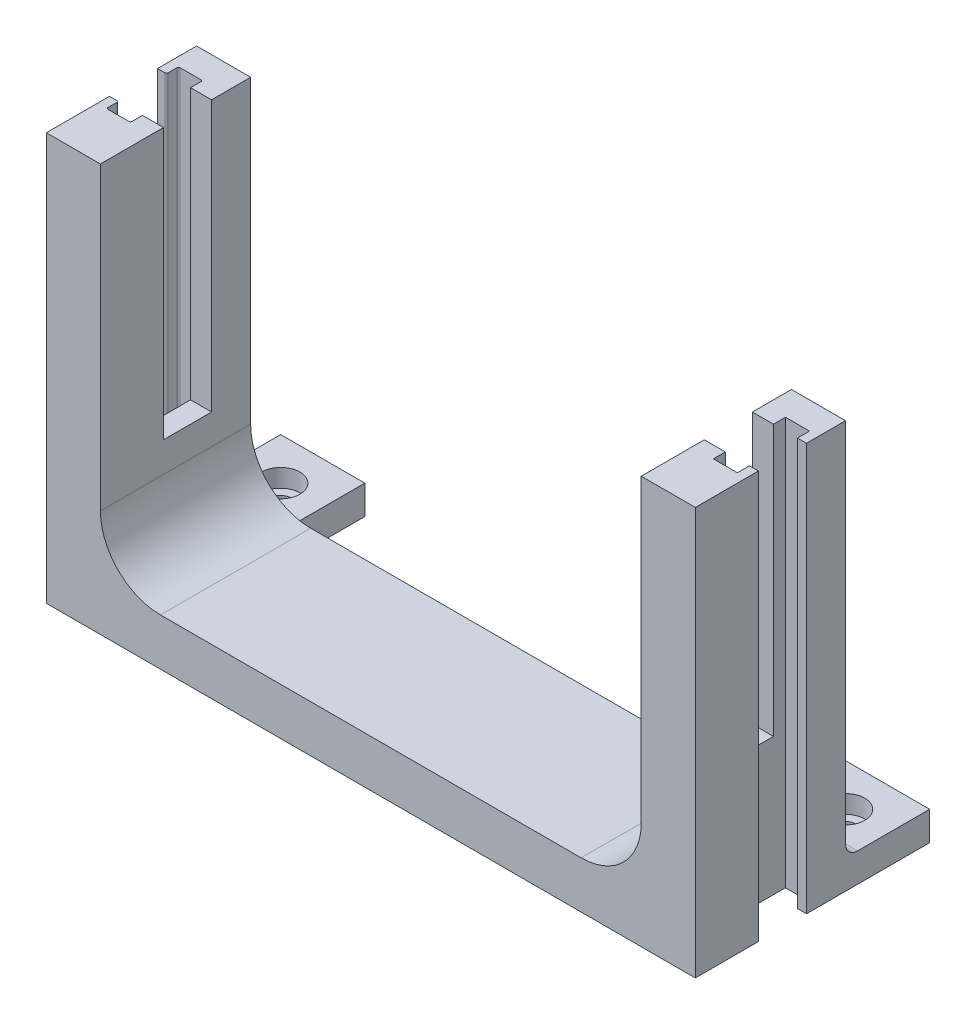
SolidWorks part; units mm, degrees
material "ABS"
ref_plane "Front Plane" through (0, 0, 0) normal (0, 0, 1) x (1, 0, 0)
ref_plane "Top Plane" through (0, 0, 0) normal (0, 1, 0) x (1, 0, 0)
ref_plane "Right Plane" through (0, 0, 0) normal (1, 0, 0) x (0, 0, -1)
sketch "Sketch1" plane through (0, 0, 0) normal (0, 0, 1) x (1, 0, 0)
  line L0 (-54, 0) -> (54, 0)
  line L1 (-54, 0) -> (-54, 67.82)
  line L2 (-54, 67.82) -> (-45, 67.82)
  line L3 (-45, 67.82) -> (-45, 7.82)
  line L4 (-45, 7.82) -> (45, 7.82)
  line L5 (0, 0) -> (0, 67.82) construction
  line L6 (54, 67.82) -> (45, 67.82)
  line L7 (45, 67.82) -> (45, 7.82)
  line L8 (54, 0) -> (54, 67.82)
  point P11 (0, 7.82)
  dimension "D1" = 45
  dimension "D2" = 60
  dimension "D3" = 7.82
  dimension "D4" = 9
extrude "Boss-Extrude1" add sketch "Sketch1" against normal blind 15
sketch "Sketch2" plane through (0, 67.82, 0) normal (0, 1, 0) x (1, 0, 0)
  line L0 (-54, 7.5) -> (-45, 7.5) construction
  line L1 (-54, 15) -> (-54, 0) construction
  line L2 (-45, 15) -> (-45, 0) construction
  line L3 (-54, 11.5) -> (-52.5, 11.5)
  line L4 (-52.5, 11.5) -> (-52.5, 13.5)
  line L5 (-52.5, 13.5) -> (-48.5, 13.5)
  line L6 (-48.5, 13.5) -> (-48.5, 1.5)
  line L7 (-54, 11.5) -> (-54, 3.5)
  line L8 (-54, 3.5) -> (-52.5, 3.5)
  line L9 (-52.5, 3.5) -> (-52.5, 1.5)
  line L10 (-52.5, 1.5) -> (-48.5, 1.5)
  point P12 (-48.5, 7.5)
  dimension "D1" = 4
  dimension "D2" = 4
  dimension "D3" = 6
  dimension "D4" = 1.5
extrude "Cut-Extrude1" cut sketch "Sketch2" against normal up to surface (67.82 mm away) up to face at (0, 0, -7.5)
sketch "Sketch3" plane through (0, 67.82, 0) normal (0, 1, 0) x (1, 0, 0)
  line L0 (-45, 11.5) -> (-48.5, 11.5)
  line L1 (-45, 15) -> (-45, 0) construction
  line L2 (-48.5, 1.5) -> (-48.5, 13.5) construction
  line L3 (-45, 3.5) -> (-48.5, 3.5)
  line L4 (-52.5, 11.5) -> (-54, 11.5) construction
  line L5 (-54, 3.5) -> (-52.5, 3.5) construction
  line L6 (-45, 11.5) -> (-45, 3.5)
  line L7 (-48.5, 11.5) -> (-48.5, 3.5)
extrude "Cut-Extrude2" cut sketch "Sketch3" against normal offset from surface (45 mm away) 15 up to face at (0, 7.82, -7.5)
fillet "Fillet1" radius 0.25 6 edges at (-52.5, 33.91, -3.5) (-52.5, 33.91, -11.5) (-52.5, 33.91, -13.5) (-48.5, 33.91, -13.5) (-52.5, 33.91, -1.5) (-48.5, 33.91, -1.5)
mirror "Mirror1" about plane through (0, 0, 0) normal (1, 0, 0) of "Cut-Extrude1"
mirror "Mirror2" about plane through (0, 0, 0) normal (1, 0, 0) of "Cut-Extrude2"
sketch "Sketch7" plane through (0, 0, 0) normal (0, 0, 1) x (1, 0, 0)
  line L8 (-54, 67.82) -> (-54, 0)
  line L9 (-54, 0) -> (54, 0)
  line L10 (54, 0) -> (54, 67.82)
  line L11 (54, 67.82) -> (45, 67.82)
  line L12 (45, 67.82) -> (45, 7.82)
  line L13 (45, 7.82) -> (-45, 7.82)
  line L14 (-45, 7.82) -> (-45, 67.82)
  line L15 (-45, 67.82) -> (-54, 67.82)
  line L16 (-54, 67.82) -> (-54, 0)
  line L17 (-54, 0) -> (54, 0)
  line L18 (54, 0) -> (54, 67.82)
  line L19 (54, 67.82) -> (45, 67.82)
  line L20 (45, 67.82) -> (45, 7.82)
  line L21 (45, 7.82) -> (-45, 7.82)
  line L22 (-45, 7.82) -> (-45, 67.82)
  line L23 (-45, 67.82) -> (-54, 67.82)
  dimension "D1" = 0
extrude "Boss-Extrude2" add sketch "Sketch7" along normal blind 7
sketch "Sketch8" plane through (0, 7.82, 0) normal (0, 1, 0) x (1, 0, 0)
  line L0 (0, 15) -> (0, -7) construction
  line L1 (45, 15) -> (-45, 15) construction
  line L2 (45, -7) -> (-45, -7) construction
  point P6 (0, 4)
sketch "Sketch11" plane through (0, 0, -15) normal (0, 0, -1) x (-1, 0, 0)
  line L8 (54, 0) -> (54, 67.82)
  line L9 (54, 67.82) -> (45, 67.82)
  line L10 (45, 67.82) -> (45, 7.82)
  line L11 (45, 7.82) -> (-45, 7.82)
  line L12 (-45, 7.82) -> (-45, 67.82)
  line L13 (-45, 67.82) -> (-54, 67.82)
  line L14 (-54, 67.82) -> (-54, 0)
  line L15 (-54, 0) -> (54, 0)
  line L16 (54, 0) -> (54, 67.82)
  line L17 (54, 67.82) -> (45, 67.82)
  line L18 (45, 67.82) -> (45, 7.82)
  line L19 (45, 7.82) -> (-45, 7.82)
  line L20 (-45, 7.82) -> (-45, 67.82)
  line L21 (-45, 67.82) -> (-54, 67.82)
  line L22 (-54, 67.82) -> (-54, 0)
  line L23 (-54, 0) -> (54, 0)
  dimension "D1" = 0
extrude "Boss-Extrude3" add sketch "Sketch11" along normal blind 3
fillet "Fillet2" radius 10 2 edges at (45, 7.82, -5.5) (-45, 7.82, -5.5)
sketch "Sketch12" plane through (0, 0, -18) normal (0, 0, 1) x (1, 0, 0)
  line L0 (-54, 4.82) -> (-54, 0)
  line L1 (-54, 67.82) -> (-54, 0) construction
  line L2 (-54, 0) -> (-40, 0)
  line L3 (-54, 0) -> (54, 0) construction
  line L4 (-40, 0) -> (-40, 4.82)
  line L5 (-40, 4.82) -> (-54, 4.82)
  line L6 (54, 0) -> (54, 4.82)
  line L7 (54, 0) -> (54, 67.82) construction
  line L8 (54, 4.82) -> (40, 4.82)
  line L9 (40, 4.82) -> (40, 0)
  line L10 (40, 0) -> (54, 0)
  line L13 (0, 0) -> (0, 7.82) construction
  dimension "D1" = 14
  dimension "D2" = 4.82
extrude "Boss-Extrude4" add sketch "Sketch12" against normal blind 14
ref_plane "Plane1" through (-47, 0, 0) normal (-1, 0, 0) x (0, 0, 1)
sketch "Sketch13" plane through (-47, 0, 0) normal (-1, 0, 0) x (0, 0, 1)
  line L0 (-32, 4.82) -> (-18, 4.82) construction
  line L1 (-32, 4.82) -> (-18, 4.82) construction
  line L2 (-25, 4.82) -> (-25, 0)
  line L3 (-3.5, 0) -> (7, 0) construction
  line L4 (-25, 4.82) -> (-21.8, 4.82)
  line L5 (-21.8, 4.82) -> (-21.8, 1.82)
  line L6 (-21.8, 1.82) -> (-23.26, 1.82)
  line L7 (-23.26, 1.82) -> (-23.26, 0)
  line L8 (-23.26, 0) -> (-25, 0)
  point P7 (-25, 4.82)
  dimension "D1" = 3
  dimension "D2" = 3.2
  dimension "D3" = 1.74
revolve "Cut-Revolve1" cut sketch "Sketch13" angle 360 about L2
mirror "Mirror3" about plane through (0, 0, 0) normal (1, 0, 0) of "Cut-Revolve1"
fillet "Fillet3" radius 2 2 edges at (-47, 4.82, -18) (47, 4.82, -18)
ref_plane "Plane2" through (0, 0, -7.5) normal (0, 0, -1) x (-1, 0, 0)
